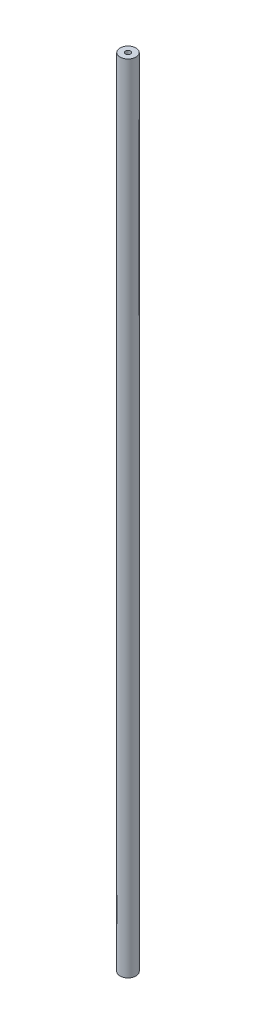
SolidWorks part; units mm, degrees
material "6061-T6 (SS)"
ref_plane "Front Plane" through (0, 0, 0) normal (0, 0, 1) x (1, 0, 0)
ref_plane "Top Plane" through (0, 0, 0) normal (0, 1, 0) x (1, 0, 0)
ref_plane "Right Plane" through (0, 0, 0) normal (1, 0, 0) x (0, 0, -1)
sketch "Sketch1" plane through (0, 0, 0) normal (0, 1, 0) x (1, 0, 0)
  circle A0 centre (0, 0) radius 6.35
  dimension "D1" = 12.7
extrude "Boss-Extrude1" add sketch "Sketch1" along normal blind 634.492
hole_wizard "#10-32 Tapped Hole1" positions "Sketch2" profile "Sketch4" tap size "#10-32" standard "ANSI Inch"
sketch "Sketch2" plane through (0, 0, 0) normal (0, -1, 0) x (-1, 0, 0)
  point P0 (0, 0)
sketch "Sketch4" plane through (0, 0, 0) normal (1, 0, 0) x (0, 0, -1)
  line L0 (0, 0) -> (0, 13.2428)
  line L1 (0, 13.2428) -> (2.0193, 12.0294)
  line L2 (2.0193, 12.0294) -> (2.0193, 0)
  line L5 (2.0193, 0) -> (0, 0)
  line L10 (0, 13.2428) -> (-2.0193, 12.0294) construction
  line L11 (0, -6.35) -> (0, 107.95) construction
  dimension "Tap Drill Dia." = 4.0386
  dimension "Tap Drill Depth" = 12.0294
  dimension "Drill Angle" = 118
cosmetic thread "Hole Thread1" parameters "D1"=9.652, "D2"=4.826
hole_wizard "#10-32 Tapped Hole2" positions "Sketch5" profile "Sketch6" tap size "#10-32" standard "ANSI Inch"
sketch "Sketch5" plane through (0, 634.492, 0) normal (0, 1, 0) x (1, 0, 0)
  point P0 (0, 0)
sketch "Sketch6" plane through (0, 634.492, 0) normal (1, 0, 0) x (0, 0, 1)
  line L0 (0, 0) -> (0, 13.2428)
  line L1 (0, 13.2428) -> (2.0193, 12.0294)
  line L2 (2.0193, 12.0294) -> (2.0193, 0)
  line L5 (2.0193, 0) -> (0, 0)
  line L10 (0, 13.2428) -> (-2.0193, 12.0294) construction
  line L11 (0, -6.35) -> (0, 107.95) construction
  dimension "Tap Drill Dia." = 4.0386
  dimension "Tap Drill Depth" = 12.0294
  dimension "Drill Angle" = 118
cosmetic thread "Hole Thread2"
